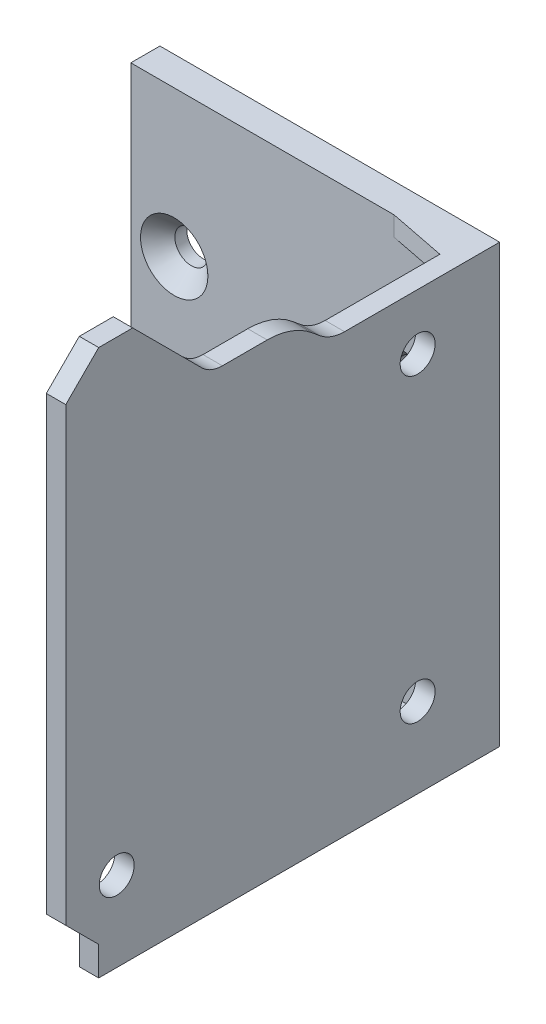
SolidWorks part; units mm, degrees
ref_plane "Front Plane" through (0, 0, 0) normal (0, 0, 1) x (1, 0, 0)
ref_plane "Top Plane" through (0, 0, 0) normal (0, 1, 0) x (1, 0, 0)
ref_plane "Right Plane" through (0, 0, 0) normal (1, 0, 0) x (0, 0, -1)
sketch "Sketch1" plane through (-17.6983, 0, 0) normal (1, 0, 0) x (0, 0, -1)
  line L2 (-911.7752, 293.9007) -> (-904.0752, 293.9007)
  line L3 (-904.0752, 293.9007) -> (-904.0752, 251.9007)
  line L4 (-904.0752, 251.9007) -> (-910.6693, 251.9007)
  line L6 (-907.2752, 289.4007) -> (-907.2752, 255.2948) construction
  line L8 (-948.7752, 301.7566) -> (-945.3811, 305.1507)
  line L10 (-941.8811, 305.1507) -> (-945.3811, 305.1507)
  line L12 (-941.8811, 305.1507) -> (-938.487, 301.7566)
  line L13 (-907.0752, 293.9007) -> (-907.0752, 255.7375) construction
  line L45 (-948.7752, 301.7566) -> (-948.7752, 255.2948)
  line L46 (-948.7752, 255.2948) -> (-945.3811, 251.9007)
  line L47 (-945.3811, 251.9007) -> (-910.6693, 251.9007)
  line L51 (-911.7752, 293.9007) -> (-920.0526, 293.9007)
  line L52 (-922.6142, 294.8286) -> (-923.3822, 295.469)
  line L53 (-928.0252, 297.1507) -> (-932.6384, 297.1507)
  line L54 (-934.7598, 298.0294) -> (-938.487, 301.7566)
  circle A3 centre (-912.5252, 288.1507) radius 1.8
  circle A6 centre (-912.5252, 257.1507) radius 1.8
  circle A9 centre (-943.5252, 257.1507) radius 1.8
  arc A32 (-922.6142, 294.8286) -> (-920.0526, 293.9007) centre (-920.0526, 297.9007) ccw
  arc A33 (-923.3822, 295.469) -> (-928.0252, 297.1507) centre (-928.0252, 289.9007) ccw
  arc A34 (-934.7598, 298.0294) -> (-932.6384, 297.1507) centre (-932.6384, 300.1507) ccw
  dimension "D2" = 3
  dimension "D6" = 0.2
extrude "Boss-Extrude1" add sketch "Sketch1" along normal blind 2
sketch "Sketch2" plane through (-17.6983, 0, 0) normal (-1, 0, 0) x (0, 0, 1)
  line L0 (907.0752, 293.9007) -> (907.0752, 255.7375) construction
  line L1 (907.0752, 293.9007) -> (907.0752, 255.7375)
  line L2 (911.7752, 293.9007) -> (904.0752, 293.9007) construction
  line L3 (907.0752, 293.9007) -> (904.0752, 293.9007)
  line L4 (904.0752, 293.9007) -> (904.0752, 251.9007) construction
  line L5 (904.0752, 293.9007) -> (904.0752, 251.9007)
  line L7 (904.0752, 251.9007) -> (907.0752, 251.9007)
  line L8 (904.0752, 251.9007) -> (910.6693, 251.9007) construction
  line L9 (907.0752, 251.9007) -> (907.0752, 255.7375)
extrude "Boss-Extrude2" add sketch "Sketch2" along normal blind 33
sketch "Sketch3" plane through (0, 293.9007, 0) normal (0, 1, 0) x (1, 0, 0)
  line L0 (24.0947, -907.0752) -> (-17.6983, -910.7252)
  line L1 (-50.6983, -907.0752) -> (-17.6983, -907.0752) construction
  line L2 (-17.6983, -910.7252) -> (-17.6983, -907.0752)
  line L3 (-17.6983, -907.0752) -> (24.0947, -907.0752)
extrude "Boss-Extrude3" add sketch "Sketch3" against normal blind 1
sketch "Sketch4" plane through (0, 251.9007, 0) normal (0, -1, 0) x (1, 0, 0)
  line L0 (-50.6983, 907.0752) -> (-17.6983, 907.0752)
  line L1 (-17.6983, 907.0752) -> (-17.6983, 945.3811)
  line L2 (-17.6983, 945.3811) -> (-15.6983, 945.3811)
  line L3 (-15.6983, 945.3811) -> (-15.6983, 904.0752)
  line L4 (-15.6983, 904.0752) -> (-50.6983, 904.0752)
  line L5 (-50.6983, 904.0752) -> (-50.6983, 907.0752) construction
  line L6 (-70.7422, 904.0752) -> (-62.4103, 904.0752) construction
  line L7 (-50.6983, 904.0752) -> (-50.6983, 907.0752)
extrude "Boss-Extrude4" add sketch "Sketch4" along normal blind 3 and the other way blind 0.0001
sketch "Sketch5" plane through (0, 248.9007, 0) normal (0, -1, 0) x (1, 0, 0)
  line L0 (11.7959, 907.0752) -> (-17.6983, 926.2281)
  line L1 (-17.6983, 907.0752) -> (-50.6983, 907.0752) construction
  line L2 (-17.6983, 945.3811) -> (-17.6983, 907.0752) construction
  line L3 (-17.6983, 926.2281) -> (-17.6983, 907.0752)
  line L4 (-17.6983, 907.0752) -> (11.7959, 907.0752)
extrude "Boss-Extrude5" add sketch "Sketch5" against normal blind 2.5
sketch "Sketch10" plane through (0, 293.9007, 0) normal (0, 1, 0) x (1, 0, 0)
  line L0 (-15.6983, -907.0752) -> (-15.6983, -910.5505)
  line L1 (-15.6983, -910.5505) -> (24.0947, -907.0752)
  line L2 (24.0947, -907.0752) -> (-15.6983, -907.0752)
extrude "Cut-Extrude1" cut sketch "Sketch10" against normal blind 3
sketch "Sketch11" plane through (0, 251.4007, 0) normal (0, 1, 0) x (1, 0, 0)
  line L3 (11.7959, -907.0752) -> (-15.6983, -907.0752)
  line L4 (-15.6983, -907.0752) -> (-15.6983, -924.9294)
  line L5 (-15.6983, -924.9294) -> (11.7959, -907.0752)
  line L6 (11.7959, -907.0752) -> (-15.6983, -907.0752)
  line L7 (-15.6983, -907.0752) -> (-15.6983, -924.9294)
  line L8 (-15.6983, -924.9294) -> (11.7959, -907.0752)
  dimension "D1" = 0
extrude "Cut-Extrude2" cut sketch "Sketch11" against normal blind 3
sketch "Sketch12" plane through (0, 0, 907.0752) normal (0, 0, 1) x (1, 0, 0)
  line L0 (-50.6983, 248.9007) -> (-50.6983, 293.9007) construction
  line L1 (-46.228, 278.8453) -> (-23.228, 278.8453) construction
  line L2 (-46.228, 278.8453) -> (-46.228, 256.8453) construction
  line L3 (-46.228, 256.8453) -> (-23.228, 256.8453) construction
  line L4 (-23.228, 278.8453) -> (-23.228, 256.8453) construction
  line L5 (-50.6983, 293.9007) -> (-17.6983, 293.9007) construction
  dimension "D1" = 23
  dimension "D2" = 22
  dimension "D3" = 4.4703
  dimension "D4" = 15.0554
hole_wizard "CSK for M3 Hex Socket Countersunk Head Screw2" positions "3DSketch4" profile "Sketch15" countersink size "M3" standard "DIN" end condition through all
sketch3d "3DSketch4"
  point P0 (-46.228, 278.8453, 907.0752)
  point P3 (-23.228, 278.8453, 907.0752)
  point P6 (-46.228, 256.8453, 907.0752)
  point P9 (-23.228, 256.8453, 907.0752)
sketch "Sketch15" plane through (-46.228, 278.8453, 907.0752) normal (1, 0, 0) x (0, -1, 0)
  line L0 (0, 0) -> (0, 3)
  line L1 (0, 3) -> (1.7, 3)
  line L2 (1.7, 3) -> (1.7, 1.77)
  line L3 (1.7, 1.77) -> (3.47, 0)
  line L5 (3.47, 0) -> (0, 0)
  line L6 (-1.7, 1.77) -> (-3.47, 0) construction
  line L11 (0, -6.35) -> (0, 107.95) construction
  dimension "Диаметр сквозного отверстия" = 3.4
  dimension "Глубина сквозного отверстия" = 3
  dimension "Диаметр передней зенковки" = 6.94
  dimension "Угол передней зенковки" = 90
sketch "Sketch16" plane through (0, 248.9007, 0) normal (0, -1, 0) x (1, 0, 0)
  line L0 (-34.1983, 907.0752) -> (-17.6983, 926.2281)
  line L1 (-17.6983, 907.0752) -> (-50.6983, 907.0752) construction
  line L2 (-17.6983, 945.3811) -> (-17.6983, 907.0752) construction
  line L3 (-17.6983, 926.2281) -> (-17.6983, 907.0752)
  line L4 (-17.6983, 907.0752) -> (-34.1983, 907.0752)
extrude "Boss-Extrude6" add sketch "Sketch16" against normal blind 2 separate body
sketch "Sketch17" plane through (0, 293.9007, 0) normal (0, 1, 0) x (1, 0, 0)
  line L0 (-17.6983, -908.2341) -> (-23.5772, -907.0752)
  line L1 (-17.6983, -907.0752) -> (-17.6983, -920.0526) construction
  line L2 (-50.6983, -907.0752) -> (-17.6983, -907.0752) construction
  line L3 (-23.5772, -907.0752) -> (-17.6983, -907.0752)
  line L4 (-17.6983, -907.0752) -> (-17.6983, -908.2341)
extrude "Boss-Extrude7" add sketch "Sketch17" against normal blind 2
